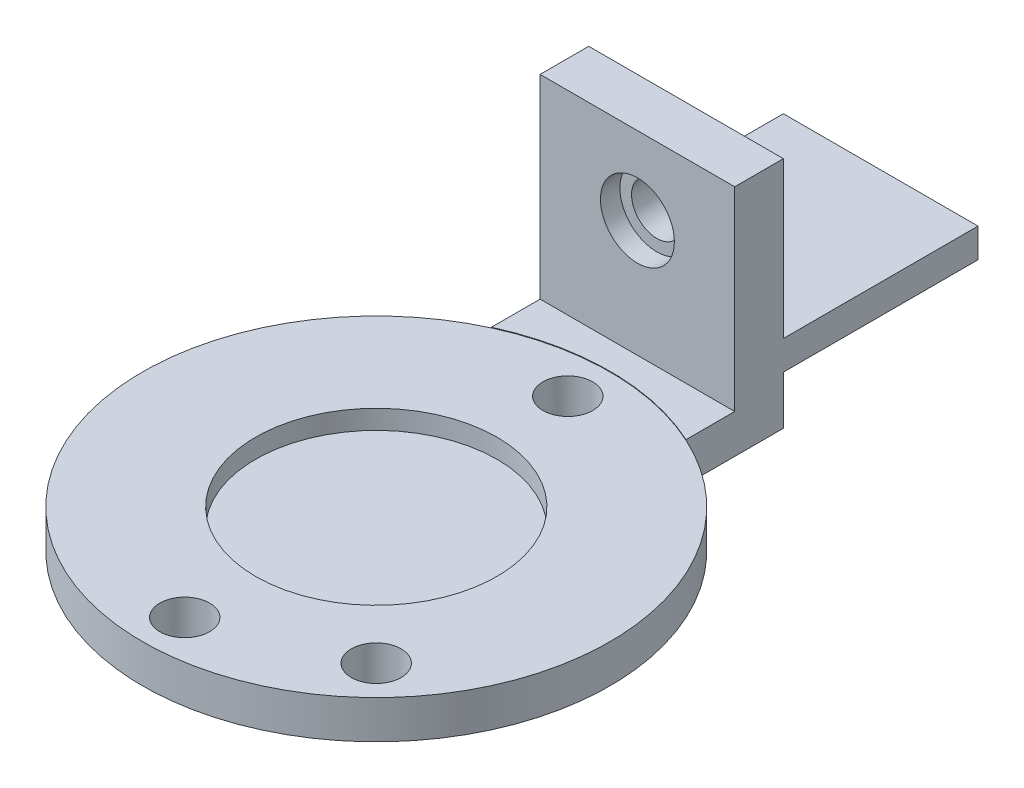
SolidWorks part; units mm, degrees
ref_plane "Front Plane" through (0, 0, 0) normal (0, 0, 1) x (1, 0, 0)
ref_plane "Top Plane" through (0, 0, 0) normal (0, 1, 0) x (1, 0, 0)
ref_plane "Right Plane" through (0, 0, 0) normal (1, 0, 0) x (0, 0, -1)
sketch "Sketch1" plane through (0, 0, 0) normal (0, 1, 0) x (1, 0, 0)
  circle A0 centre (0, 0) radius 30.5
extrude "Boss-Extrude1" add sketch "Sketch1" along normal blind 5
sketch "Sketch2" plane through (0, 5, 0) normal (0, 1, 0) x (1, 0, 0)
  circle A0 centre (0, 0) radius 15.75
extrude "Cut-Extrude1" cut sketch "Sketch2" against normal blind 2.5
sketch "Sketch3" plane through (0, 0, 0) normal (0, -1, 0) x (1, 0, 0)
  circle A0 centre (0, 0) radius 15.75
extrude "Boss-Extrude2" add sketch "Sketch3" along normal blind 2.5
sketch "Sketch4" plane through (0, 0, 0) normal (0, -1, 0) x (-1, 0, 0)
  circle A0 centre (0, 25) radius 3.25
  point P0 (0, 25)
  dimension "D1" = 25
extrude "Cut-Extrude2" cut sketch "Sketch4" against normal blind 5.08
sketch "Sketch5" plane through (0, 0, 0) normal (0, -1, 0) x (1, 0, 0)
  circle A0 centre (0, 25) radius 3.25
  point P0 (0, 25)
  dimension "D1" = 25
extrude "Cut-Extrude3" cut sketch "Sketch5" against normal blind 5.08
sketch "Sketch6" plane through (0, 0, 0) normal (0, -1, 0) x (1, 0, 0)
  circle A0 centre (0, 25) radius 3.25 construction
  circle A1 centre (17.6745, 17.6809) radius 3.25
  point P0 (17.6745, 17.6809)
  dimension "D1" = 25
  dimension "D2" = 19.13
extrude "Cut-Extrude4" cut sketch "Sketch6" against normal blind 5.08
sketch "Sketch7" plane through (0, 0, 0) normal (0, -1, 0) x (1, 0, 0)
  line L0 (0, 0) -> (0, -30.5)
  line L2 (-12.7, -27.7301) -> (12.7, -27.7301)
  line L3 (-12.7, -27.7301) -> (-12.7, -40.4301)
  line L4 (-12.7, -40.4301) -> (12.7, -40.4301)
  line L5 (12.7, -27.7301) -> (12.7, -40.4301)
  circle A0 centre (0, 0) radius 30.5 construction
  circle M8 centre (0, 0) radius 30.5
  dimension "D1" = 25.4
  dimension "D2" = 12.7
  dimension "D3" = 12.7
extrude "Boss-Extrude3" add sketch "Sketch7" against normal blind 5.08 contours L5 L3 L4 M8
sketch "Sketch8" plane through (0, 5.08, 0) normal (0, 1, 0) x (1, 0, 0)
  line L0 (12.7, 27.7301) -> (12.7, 40.4301) construction
  line L1 (-12.7, 40.4301) -> (12.7, 40.4301)
  line L2 (-12.7, 40.4301) -> (-12.7, 34.0801)
  line L3 (-12.7, 34.0801) -> (12.7, 34.0801)
  line L4 (12.7, 40.4301) -> (12.7, 34.0801)
extrude "Boss-Extrude4" add sketch "Sketch8" along normal blind 25.4
sketch "Sketch9" plane through (0, 0, -40.4301) normal (0, 0, -1) x (-1, 0, 0)
  line L0 (12.7, 30.48) -> (12.7, 0) construction
  line L1 (12.7, 6.35) -> (-12.7, 6.35)
  line L2 (12.7, 6.35) -> (12.7, 10.16)
  line L3 (12.7, 10.16) -> (-12.7, 10.16)
  line L4 (-12.7, 6.35) -> (-12.7, 10.16)
  line L5 (-12.7, 30.48) -> (-12.7, 0) construction
  line L6 (12.7, 0) -> (-12.7, 0) construction
  dimension "D1" = 3.81
  dimension "D2" = 6.35
extrude "Boss-Extrude5" add sketch "Sketch9" along normal blind 25.4
sketch "Sketch10" plane through (0, 0, -40.4301) normal (0, 0, -1) x (-1, 0, 0)
  line L0 (0, 10.16) -> (0, 30.48)
  line L1 (12.7, 10.16) -> (-12.7, 10.16) construction
  line L2 (-12.7, 30.48) -> (12.7, 30.48) construction
  circle A0 centre (0, 20.32) radius 3.302
  dimension "D1" = 10.16
extrude "Cut-Extrude5" cut sketch "Sketch10" against normal blind 7.62 contours A0
sketch "Sketch12" plane through (0, 0, -34.0801) normal (0, 0, 1) x (1, 0, 0)
  circle A0 centre (0, 20.32) radius 4.826
extrude "Cut-Extrude6" cut sketch "Sketch12" against normal blind 2.54
